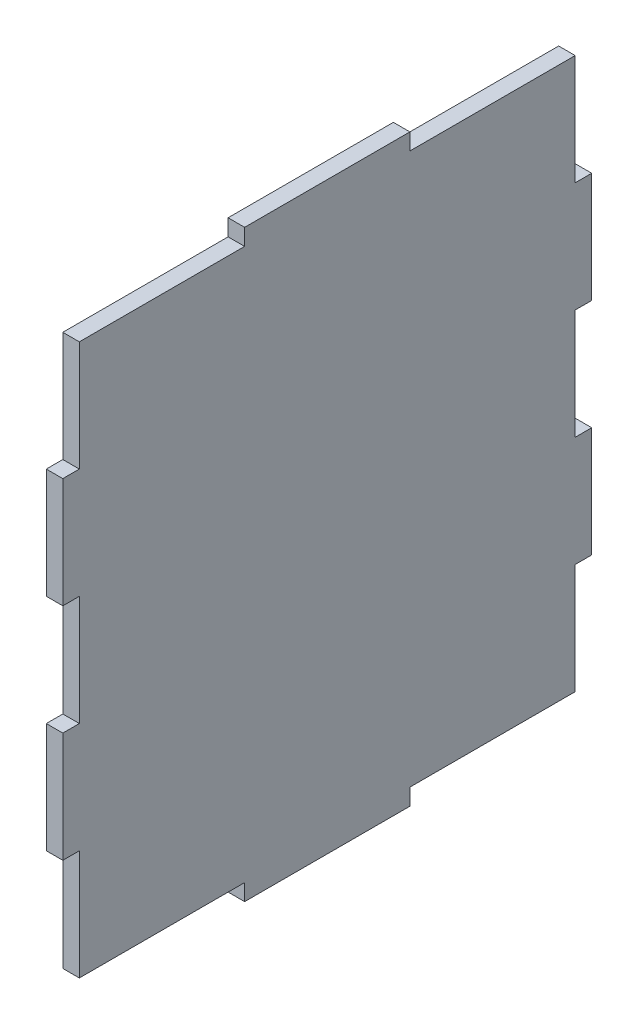
SolidWorks part; units mm, degrees
ref_plane "Front Plane" through (0, 0, 0) normal (0, 0, 1) x (1, 0, 0)
ref_plane "Top Plane" through (0, 0, 0) normal (0, 1, 0) x (1, 0, 0)
ref_plane "Right Plane" through (0, 0, 0) normal (1, 0, 0) x (0, 0, -1)
sketch "Sketch1" plane through (0, 0, 0) normal (1, 0, 0) x (0, 0, -1)
  line L0 (33.5849, 51.6038) -> (63.5849, 51.6038)
  line L1 (-26.4151, 51.6038) -> (3.5849, 51.6038)
  line L2 (-26.4151, 51.6038) -> (-26.4151, 31.6038)
  line L3 (-26.4151, -48.3962) -> (3.5849, -48.3962)
  line L4 (63.5849, 51.6038) -> (63.5849, 31.6038)
  line L5 (63.5849, -8.3962) -> (66.5849, -8.3962)
  line L6 (3.5849, 51.6038) -> (3.5849, 54.6038)
  line L7 (3.5849, 54.6038) -> (33.5849, 54.6038)
  line L8 (33.5849, 51.6038) -> (33.5849, 54.6038)
  line L9 (63.5849, 31.6038) -> (66.5849, 31.6038)
  line L10 (63.5849, -28.3962) -> (63.5849, -48.3962)
  line L11 (63.5849, 11.6038) -> (66.5849, 11.6038)
  line L12 (66.5849, 31.6038) -> (66.5849, 11.6038)
  line L13 (66.5849, -8.3962) -> (66.5849, -28.3962)
  line L14 (63.5849, -28.3962) -> (66.5849, -28.3962)
  line L15 (63.5849, 11.6038) -> (63.5849, -8.3962)
  line L16 (33.5849, -48.3962) -> (63.5849, -48.3962)
  line L17 (-26.4151, 11.6038) -> (-29.4151, 11.6038)
  line L18 (33.5849, -48.3962) -> (33.5849, -51.3962)
  line L19 (33.5849, -51.3962) -> (3.5849, -51.3962)
  line L20 (3.5849, -48.3962) -> (3.5849, -51.3962)
  line L21 (-26.4151, -28.3962) -> (-29.4151, -28.3962)
  line L22 (-26.4151, -28.3962) -> (-26.4151, -48.3962)
  line L23 (-26.4151, -8.3962) -> (-29.4151, -8.3962)
  line L24 (-29.4151, -28.3962) -> (-29.4151, -8.3962)
  line L25 (-29.4151, 11.6038) -> (-29.4151, 31.6038)
  line L26 (-26.4151, 31.6038) -> (-29.4151, 31.6038)
  line L27 (-26.4151, 11.6038) -> (-26.4151, -8.3962)
  point P20 (33.5849, -49.8962)
  point P25 (-27.9151, -28.3962)
  dimension "D1" = 3
  dimension "D2" = 30
  dimension "D3" = 30
  dimension "D4" = 3
  dimension "D5" = 20
  dimension "D6" = 20
extrude "Boss-Extrude1" add sketch "Sketch1" along normal blind 3
